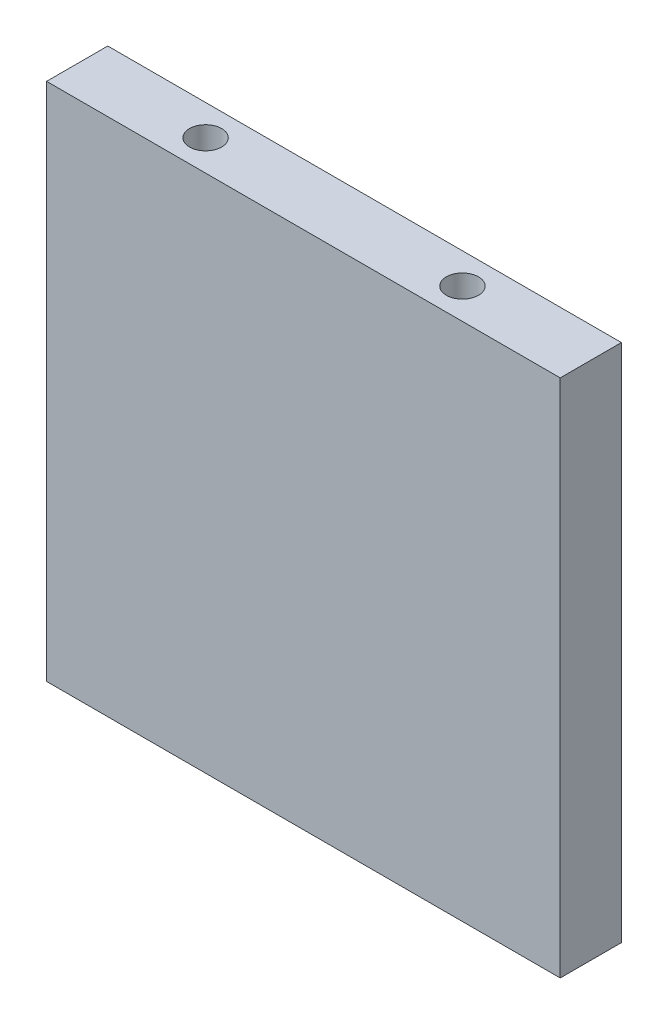
SolidWorks part; units mm, degrees
ref_plane "Plano frontal" through (0, 0, 0) normal (0, 0, 1) x (1, 0, 0)
ref_plane "Plano superior" through (0, 0, 0) normal (0, 1, 0) x (1, 0, 0)
ref_plane "Plano direito" through (0, 0, 0) normal (1, 0, 0) x (0, 0, -1)
sketch "Esboço1" plane through (0, 0, 0) normal (0, 0, 1) x (1, 0, 0)
  line L0 (40, 40.475) -> (-40, -40.475) construction
  line L1 (-40, 40.475) -> (40, 40.475)
  line L2 (-40, 40.475) -> (-40, -40.475)
  line L3 (-40, -40.475) -> (40, -40.475)
  line L4 (40, 40.475) -> (40, -40.475)
  dimension "D1" = 80
  dimension "D2" = 80.95
extrude "Ressalto-extrusão1" add sketch "Esboço1" along normal blind 9.53
sketch "Esboço2" plane through (0, 40.475, 0) normal (0, 1, 0) x (1, 0, 0)
  line L0 (0, 0) -> (0, -9.53) construction
  line L1 (40, -9.53) -> (-40, -9.53) construction
  line L2 (0, -9.53) -> (0, -4.765) construction
  line L3 (0, -4.765) -> (4.2052, -4.765) construction
  circle A0 centre (-20, -4.7625) radius 2.5
  circle A1 centre (20, -4.7625) radius 2.5
  dimension "D4" = 5
  dimension "D5" = 5
  dimension "D1" = 40
  dimension "D2" = 20
  dimension "D3" = 4.7625
extrude "Corte-extrusão1" cut sketch "Esboço2" against normal blind 20
sketch "Esboço3" plane through (0, -40.475, 0) normal (0, -1, 0) x (1, 0, 0)
  circle A0 centre (-20, 4.7625) radius 2.5
  circle A1 centre (20, 5) radius 2.5
  dimension "D1" = 5
  dimension "D2" = 5
  dimension "D3" = 5
  dimension "D4" = 4.7625
  dimension "D5" = 20
  dimension "D6" = 20
extrude "Corte-extrusão2" cut sketch "Esboço3" against normal blind 20
